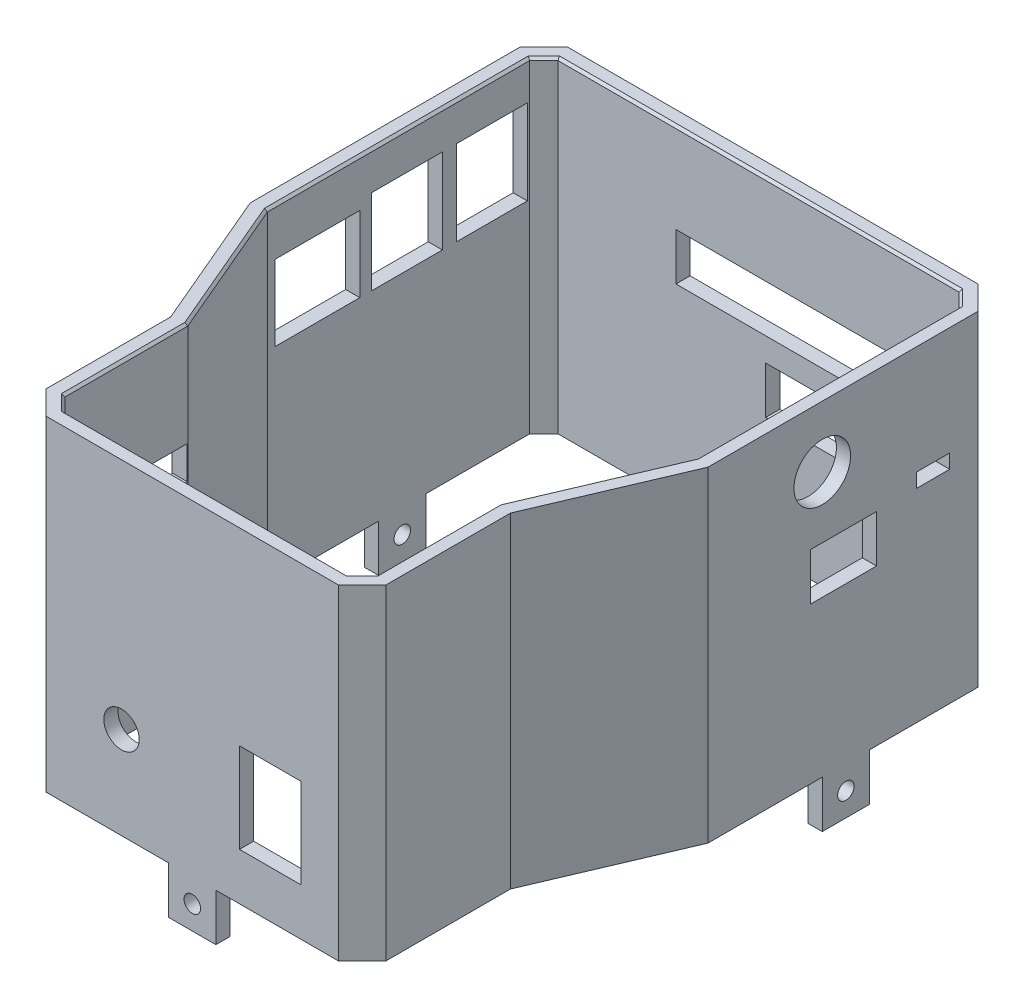
SolidWorks part; units mm, degrees
material "PETG"
ref_plane "Front Plane" through (0, 0, 0) normal (0, 0, 1) x (1, 0, 0)
ref_plane "Top Plane" through (0, 0, 0) normal (0, 1, 0) x (1, 0, 0)
ref_plane "Right Plane" through (0, 0, 0) normal (1, 0, 0) x (0, 0, -1)
sketch "Sketch1" plane through (0, 0, 0) normal (0, 1, 0) x (1, 0, 0)
  line L0 (-42.2601, -28.5633) -> (-31.2399, -54.4367)
  line L1 (-42.5, -28) -> (42.5, -28) construction
  line L2 (-42.5, -27.3877) -> (-42.5, 25)
  line L3 (-39.5, 28) -> (39.5, 28)
  line L4 (42.5, -27.3877) -> (42.5, 25)
  line L5 (-42.5, -28) -> (42.5, 28) construction
  line L6 (-42.5, 28) -> (42.5, -28) construction
  line L7 (-30, -85) -> (30, -85)
  line L8 (-31, -85) -> (-31, -43) construction
  line L9 (-31, -43) -> (31, -43) construction
  line L10 (31, -85) -> (31, -43) construction
  line L11 (-31, -85) -> (31, -43) construction
  line L12 (-31, -43) -> (31, -85) construction
  line L13 (-31, -55.6123) -> (-31, -84)
  line L14 (42.2601, -28.5633) -> (31.2399, -54.4367)
  line L15 (31, -55.6123) -> (31, -84)
  arc A0 (39.5, 28) -> (42.5, 25) centre (39.5, 25) cw
  arc A1 (-42.5, 25) -> (-39.5, 28) centre (-39.5, 25) cw
  arc A2 (-30, -85) -> (-31, -84) centre (-30, -84) cw
  arc A3 (30, -85) -> (31, -84) centre (30, -84) ccw
  arc A4 (-31.2399, -54.4367) -> (-31, -55.6123) centre (-34, -55.6123) cw
  arc A5 (31.2399, -54.4367) -> (31, -55.6123) centre (34, -55.6123) ccw
  arc A6 (42.2601, -28.5633) -> (42.5, -27.3877) centre (39.5, -27.3877) ccw
  arc A7 (-42.2601, -28.5633) -> (-42.5, -27.3877) centre (-39.5, -27.3877) cw
  point P0 (0, 0)
  point P12 (0, -64)
  point P31 (-31, -55)
  point P34 (31, -55)
  dimension "D3" = 3
  dimension "D8" = 1
  dimension "D9" = 3
  dimension "D1" = 85
  dimension "D2" = 56
  dimension "D4" = 62
  dimension "D5" = 42
  dimension "D6" = 15
  dimension "D7" = 30
sketch "Sketch3" plane through (0, 0, 0) normal (0, 1, 0) x (1, 0, 0)
  line L22 (-42.5, 28) -> (42.5, 28)
  line L23 (42.5, 28) -> (42.5, -28)
  line L24 (42.5, -28) -> (31, -55)
  line L55 (31, -55) -> (31, -85)
  line L56 (31, -85) -> (-31, -85)
  line L57 (-31, -85) -> (-31, -55)
  line L58 (-31, -55) -> (-42.5, -28)
  line L59 (-42.5, -28) -> (-42.5, 28)
  line L60 (-42.5, -27.3877) -> (-42.5, 25) construction
  line L61 (-42.2601, -28.5633) -> (-31.2399, -54.4367) construction
  line L62 (-31, -55.6123) -> (-31, -84) construction
  line L63 (31, -55.6123) -> (31, -84) construction
  line L64 (42.2601, -28.5633) -> (31.2399, -54.4367) construction
sketch "Sketch4" plane through (0, 0, 0) normal (0, 1, 0) x (1, 0, 0)
  line L0 (-42.5, 28) -> (42.5, 28) construction
  line L1 (42.5, 28) -> (42.5, -28) construction
  line L2 (42.5, -28) -> (31, -55) construction
  line L3 (31, -55) -> (31, -85) construction
  line L4 (31, -85) -> (-31, -85) construction
  line L5 (-31, -85) -> (-31, -55) construction
  line L6 (-31, -55) -> (-42.5, -28) construction
  line L7 (-42.5, -28) -> (-42.5, 28) construction
  line L8 (-42.5, 28) -> (42.5, 28) construction
  line L9 (42.5, 28) -> (42.5, -28) construction
  line L10 (42.5, -28) -> (31, -55) construction
  line L11 (31, -55) -> (31, -85) construction
  line L12 (31, -85) -> (-31, -85) construction
  line L13 (-31, -85) -> (-31, -55) construction
  line L14 (-31, -55) -> (-42.5, -28) construction
  line L15 (-42.5, -28) -> (-42.5, 28) construction
  line L16 (-45.5, 30) -> (45.5, 30)
  line L17 (45.5, 30) -> (45.5, -28.6123)
  line L18 (45.5, -28.6123) -> (33, -57.9601)
  line L19 (33, -57.9601) -> (33, -87)
  line L20 (33, -87) -> (-33, -87)
  line L21 (-33, -87) -> (-33, -57.9601)
  line L22 (-33, -57.9601) -> (-45.5, -28.6123)
  line L23 (-45.5, -28.6123) -> (-45.5, 30)
  line L24 (-48.5, 33) -> (48.5, 33)
  line L25 (48.5, 33) -> (48.5, -29.2246)
  line L26 (48.5, -29.2246) -> (36, -58.5724)
  line L27 (36, -58.5724) -> (36, -90)
  line L28 (36, -90) -> (-36, -90)
  line L29 (-36, -90) -> (-36, -58.5724)
  line L30 (-36, -58.5724) -> (-48.5, -29.2246)
  line L31 (-48.5, -29.2246) -> (-48.5, 33)
  dimension "D1" = 3
  dimension "D2" = 3
  dimension "D3" = 2
  dimension "D4" = 3
  dimension "D5" = 3
  dimension "D6" = 2
  dimension "D7" = 2
  dimension "D8" = 2
  dimension "D9" = 3
extrude "Boss-Extrude2" add sketch "Sketch4" along normal blind 69
chamfer "Chamfer1" distance 3 angle 45 4 edges at (-33, 34.5, 87) (33, 34.5, 87) (45.5, 34.5, -30) (-45.5, 34.5, -30)
chamfer "Chamfer2" distance 5 angle 45 4 edges at (48.5, 34.5, -33) (36, 34.5, 90) (-36, 34.5, 90) (-48.5, 34.5, -33)
sketch "Sketch5" plane through (0, 0, 0) normal (0, 1, 0) x (1, 0, 0)
  line L0 (43.5, 33) -> (-43.5, 33) construction
  line L1 (5, 33) -> (-5, 33)
  line L2 (5, 33) -> (5, 30)
  line L3 (5, 30) -> (-5, 30)
  line L4 (-5, 33) -> (-5, 30)
  line L5 (5, 33) -> (-5, 30) construction
  line L6 (5, 30) -> (-5, 33) construction
  line L7 (42.5, 30) -> (-42.5, 30) construction
  line L8 (-45.5, 27) -> (-45.5, -28.6123) construction
  line L9 (-45.5, 5) -> (-48.5, 5)
  line L10 (-45.5, 5) -> (-45.5, -5)
  line L11 (-45.5, -5) -> (-48.5, -5)
  line L12 (-48.5, 5) -> (-48.5, -5)
  line L13 (-45.5, 5) -> (-48.5, -5) construction
  line L14 (-45.5, -5) -> (-48.5, 5) construction
  line L15 (-48.5, 28) -> (-48.5, -29.2246) construction
  line L16 (-30, -87) -> (30, -87) construction
  line L17 (5, -87) -> (-5, -87)
  line L18 (5, -87) -> (5, -90)
  line L19 (5, -90) -> (-5, -90)
  line L20 (-5, -87) -> (-5, -90)
  line L21 (5, -87) -> (-5, -90) construction
  line L22 (5, -90) -> (-5, -87) construction
  line L23 (-31, -90) -> (31, -90) construction
  line L24 (48.5, -29.2246) -> (48.5, 28) construction
  line L25 (48.5, 5) -> (45.5, 5)
  line L26 (48.5, 5) -> (48.5, -5)
  line L27 (48.5, -5) -> (45.5, -5)
  line L28 (45.5, 5) -> (45.5, -5)
  line L29 (48.5, 5) -> (45.5, -5) construction
  line L30 (48.5, -5) -> (45.5, 5) construction
  line L31 (45.5, -28.6123) -> (45.5, 27) construction
  point P4 (0, 31.5)
  point P13 (-47, 0)
  point P22 (0, -88.5)
  point P33 (47, 0)
  dimension "D1" = 10
  dimension "D2" = 10
  dimension "D3" = 10
  dimension "D4" = 10
extrude "Boss-Extrude3" add sketch "Sketch5" against normal blind 10
sketch "Sketch6" plane through (-48.5, 0, 0) normal (-1, 0, 0) x (0, 0, 1)
  line L0 (-5, -10) -> (5, -10) construction
  line L3 (0, -10) -> (0, 49990) construction
  line L4 (-5, -5) -> (49995, -5) construction
  line L5 (-5, -10) -> (-5, 0) construction
  circle A0 centre (0, -5) radius 1.75
  point P10 (0, -10)
  point P11 (-5, -5)
  dimension "D1" = 3.5
extrude "Cut-Extrude1" cut sketch "Sketch6" against normal through all
sketch "Sketch7" plane through (0, 0, -33) normal (0, 0, -1) x (-1, 0, 0)
  line L0 (0, -10) -> (0, 49990) construction
  line L1 (-5, -10) -> (5, -10) construction
  line L2 (5, -5) -> (-49995, -5) construction
  line L3 (5, -10) -> (5, 0) construction
  circle A0 centre (0, -5) radius 1.75
  point P4 (0, -10)
  point P9 (5, -5)
  dimension "D1" = 3.5
extrude "Cut-Extrude2" cut sketch "Sketch7" against normal through all
sketch "Sketch8" plane through (0, 0, -33) normal (0, 0, -1) x (-1, 0, 0)
  line L5 (-48.5, 0) -> (-48.5, 69) construction
  line L6 (-39.5, 50) -> (17.5, 50)
  line L7 (-39.5, 50) -> (-39.5, 40)
  line L12 (-39.5, 40) -> (17.5, 40)
  line L25 (17.5, 50) -> (17.5, 40)
  line L26 (-43.5, 69) -> (43.5, 69) construction
  line L32 (-36.5, 35) -> (-1.5, 35)
  line L33 (-36.5, 35) -> (-36.5, 25)
  line L34 (-36.5, 25) -> (-1.5, 25)
  line L35 (-1.5, 35) -> (-1.5, 25)
  dimension "D1" = 57
  dimension "D2" = 10
  dimension "D3" = 9
  dimension "D4" = 29
  dimension "D5" = 12
  dimension "D6" = 5
  dimension "D7" = 35
  dimension "D8" = 10
extrude "Cut-Extrude3" cut sketch "Sketch8" against normal up to next
sketch "Sketch10" plane through (-48.5, 0, 0) normal (-1, 0, 0) x (0, 0, 1)
  line L10 (-33, 0) -> (-33, 69) construction
  line L11 (-26.5, 61) -> (-11.5, 61)
  line L12 (-26.5, 61) -> (-26.5, 43)
  line L13 (-26.5, 43) -> (-11.5, 43)
  line L14 (-11.5, 61) -> (-11.5, 43)
  line L15 (-8.5, 61) -> (6.5, 61)
  line L33 (-8.5, 61) -> (-8.5, 43)
  line L34 (-8.5, 43) -> (6.5, 43)
  line L35 (6.5, 61) -> (6.5, 43)
  line L36 (27, 59) -> (9, 59)
  line L37 (27, 59) -> (27, 43)
  line L38 (27, 43) -> (9, 43)
  line L39 (9, 59) -> (9, 43)
  line L40 (-33, 69) -> (-28, 69) construction
  dimension "D1" = 6.5
  dimension "D2" = 18
  dimension "D3" = 8
  dimension "D4" = 15
  dimension "D5" = 15
  dimension "D6" = 3
  dimension "D7" = 2.5
  dimension "D8" = 18
  dimension "D9" = 16
extrude "Cut-Extrude4" cut sketch "Sketch10" against normal up to next
sketch "Sketch12" plane through (-36, 0, 0) normal (-1, 0, 0) x (0, 0, 1)
  line L0 (58.5724, 69) -> (58.5724, 0) construction
  line L1 (68.5, 40.6) -> (84, 40.6) construction
  line L6 (68.5, 40.6) -> (84, 40.6) construction
  line L7 (58.0724, 47) -> (70.0724, 47)
  line L8 (58.0724, 47) -> (58.0724, 40)
  line L9 (58.0724, 40) -> (70.0724, 40)
  line L15 (70.0724, 47) -> (70.0724, 40)
  line L16 (58.5724, 0) -> (85, 0) construction
  dimension "D1" = 12
  dimension "D2" = 7
  dimension "D3" = 40
  dimension "D4" = 0.5
extrude "Cut-Extrude5" cut sketch "Sketch12" against normal up to next and the other way through all
sketch "Sketch14" plane through (48.5, 0, 0) normal (1, 0, 0) x (0, 0, -1)
  circle A0 centre (-5, 56) radius 6
  dimension "D1" = 12
  dimension "D2" = 56
  dimension "D3" = 5
extrude "Cut-Extrude6" cut sketch "Sketch14" against normal up to next
sketch "Sketch15" plane through (0, 0, 90) normal (0, 0, 1) x (1, 0, 0)
  line L1 (23, 10) -> (10, 10)
  line L2 (23, 10) -> (23, 29)
  line L3 (23, 29) -> (10, 29)
  line L4 (10, 10) -> (10, 29)
  dimension "D1" = 13
  dimension "D2" = 19
  dimension "D3" = 10
  dimension "D4" = 10
extrude "Cut-Extrude7" cut sketch "Sketch15" against normal up to next
sketch "Sketch16" plane through (48.5, 0, 0) normal (1, 0, 0) x (0, 0, -1)
  line L1 (-7.5, 43) -> (6.5, 43)
  line L2 (-7.5, 43) -> (-7.5, 33)
  line L3 (-7.5, 33) -> (6.5, 33)
  line L4 (6.5, 43) -> (6.5, 33)
  line L7 (33, 69) -> (33, 0) construction
  line L11 (-29.2246, 69) -> (28, 69) construction
  dimension "D1" = 26.5
  dimension "D2" = 14
  dimension "D3" = 10
  dimension "D4" = 26
extrude "Cut-Extrude8" cut sketch "Sketch16" against normal up to next
sketch "Sketch18" plane through (48.5, 0, 0) normal (1, 0, 0) x (0, 0, -1)
  line L1 (15, 43) -> (22, 43)
  line L2 (15, 43) -> (15, 46)
  line L3 (15, 46) -> (22, 46)
  line L4 (22, 43) -> (22, 46)
  line L5 (33, 69) -> (33, 0) construction
  line L6 (6.5, 43) -> (-7.5, 43) construction
  dimension "D1" = 7
  dimension "D2" = 3
  dimension "D3" = 11
  dimension "D4" = 3
extrude "Cut-Extrude9" cut sketch "Sketch18" against normal up to next
chamfer "Chamfer3" distance 0.5 angle 45 12 edges at (45.5, 69, 0.8061) (44, 69, -28.5) (0, 69, -30) (-44, 69, -28.5) (-45.5, 69, 0.8061) (-39.25, 69, 43.2862) (-33, 69, 70.9801) (-31.5, 69, 85.5) (0, 69, 87) (31.5, 69, 85.5) (33, 69, 70.9801) (39.25, 69, 43.2862)
sketch "Sketch19" plane through (0, 0, 90) normal (0, 0, 1) x (1, 0, 0)
  line L0 (10, 19.5) -> (-49990, 19.5) construction
  line L1 (10, 29) -> (10, 10) construction
  circle A0 centre (-15, 19.5) radius 3.75
  point P6 (10, 19.5)
  point P7 (0, 0)
  dimension "D1" = 7.5
  dimension "D2" = 15
extrude "Cut-Extrude10" cut sketch "Sketch19" against normal up to next
